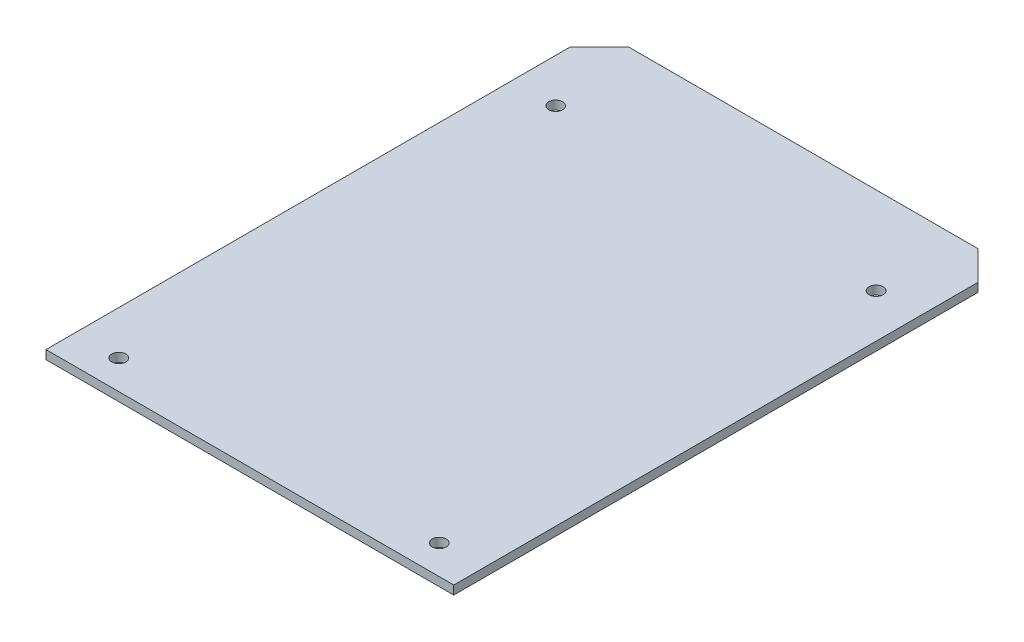
SolidWorks part; units mm, degrees
material "Beech"
ref_plane "Front Plane" through (0, 0, 0) normal (0, 0, 1) x (1, 0, 0)
ref_plane "Top Plane" through (0, 0, 0) normal (0, 1, 0) x (1, 0, 0)
ref_plane "Right Plane" through (0, 0, 0) normal (1, 0, 0) x (0, 0, -1)
sketch "Sketch1" plane through (0, 0, 0) normal (0, 1, 0) x (1, 0, 0)
  line L1 (70, -95) -> (-70, -95)
  line L2 (70, -95) -> (70, 95)
  line L3 (70, 95) -> (-70, 95)
  line L4 (-70, -95) -> (-70, 95)
  line L5 (70, -95) -> (-70, 95) construction
  line L6 (70, 95) -> (-70, -95) construction
  point P0 (0, 0)
  dimension "D1" = 140
  dimension "D2" = 190
extrude "Boss-Extrude1" add sketch "Sketch1" along normal blind 3
sketch "Sketch2" plane through (0, 3, 0) normal (0, 1, 0) x (1, 0, 0)
  line L0 (-55, -85) -> (55, -85) construction
  line L1 (0, -85) -> (0, -95) construction
  line L2 (-70, -95) -> (70, -95) construction
  line L3 (-70, 95) -> (-70, -95) construction
  line L4 (-55, 65) -> (55, 65) construction
  line L5 (0, 65) -> (0, -85) construction
  line L6 (70, 95) -> (-70, 95) construction
  point P0 (-55, -85)
  point P1 (55, -85)
  point P10 (-55, 65)
  point P11 (55, 65)
  dimension "D1" = 15
  dimension "D2" = 10
  dimension "D3" = 15
  dimension "D4" = 30
  dimension "D5" = 150
hole_wizard "M4 Clearance Hole1" positions "Sketch3" profile "Sketch5" hole size "M4" standard "ISO" end condition through all
sketch "Sketch3" plane through (0, 3, 0) normal (0, 1, 0) x (1, 0, 0)
  point P0 (-55, -85)
  point P3 (55, -85)
  point P6 (-55, 65)
  point P9 (55, 65)
sketch "Sketch5" plane through (-55, 3, 85) normal (1, 0, 0) x (0, 0, 1)
  line L0 (0, 0) -> (0, 3)
  line L1 (0, 3) -> (2.4, 3)
  line L2 (2.4, 3) -> (2.4, 0)
  line L5 (2.4, 0) -> (0, 0)
  line L11 (0, -6.35) -> (0, 107.95) construction
  dimension "Thru Hole Dia." = 4.8
  dimension "Thru Hole Depth" = 3
chamfer "Chamfer1" distance 10 angle 45 2 edges at (70, 1.5, -95) (-70, 1.5, -95)
